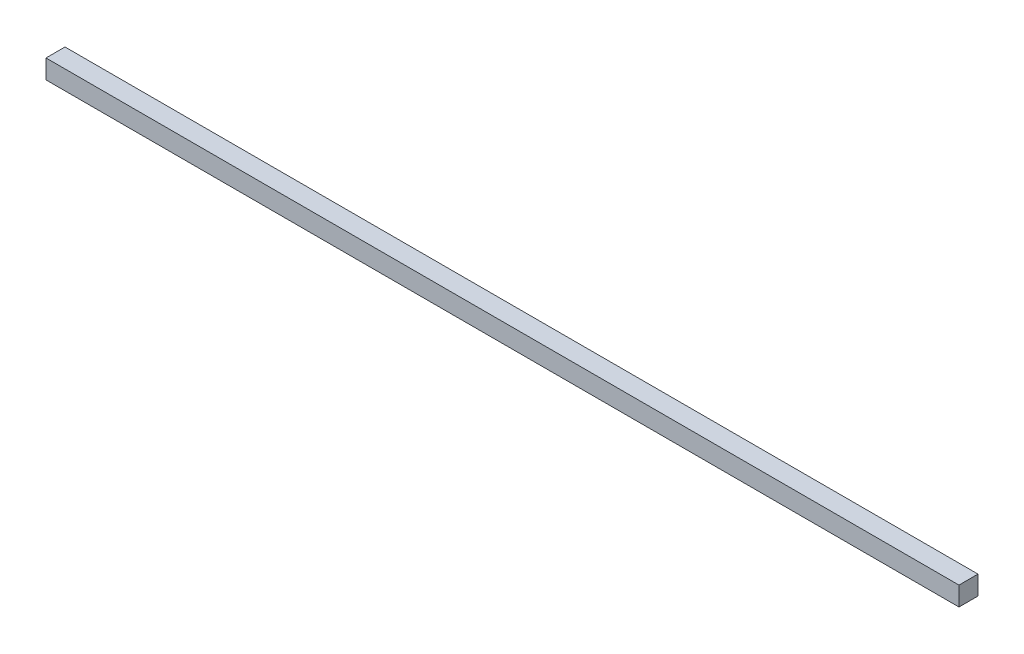
SolidWorks part; units mm, degrees
ref_plane "Front Plane" through (0, 0, 0) normal (0, 0, 1) x (1, 0, 0)
ref_plane "Top Plane" through (0, 0, 0) normal (0, 1, 0) x (1, 0, 0)
ref_plane "Right Plane" through (0, 0, 0) normal (1, 0, 0) x (0, 0, -1)
sketch "Sketch1" plane through (0, 0, 0) normal (0, 1, 0) x (1, 0, 0)
  line L1 (0, 0) -> (152.4, 0)
  line L2 (0, 0) -> (0, 3.175)
  line L3 (0, 3.175) -> (152.4, 3.175)
  line L4 (152.4, 0) -> (152.4, 3.175)
  dimension "D1" = 3.175
  dimension "D2" = 152.4
extrude "Boss-Extrude1" add sketch "Sketch1" along normal blind 3.175
